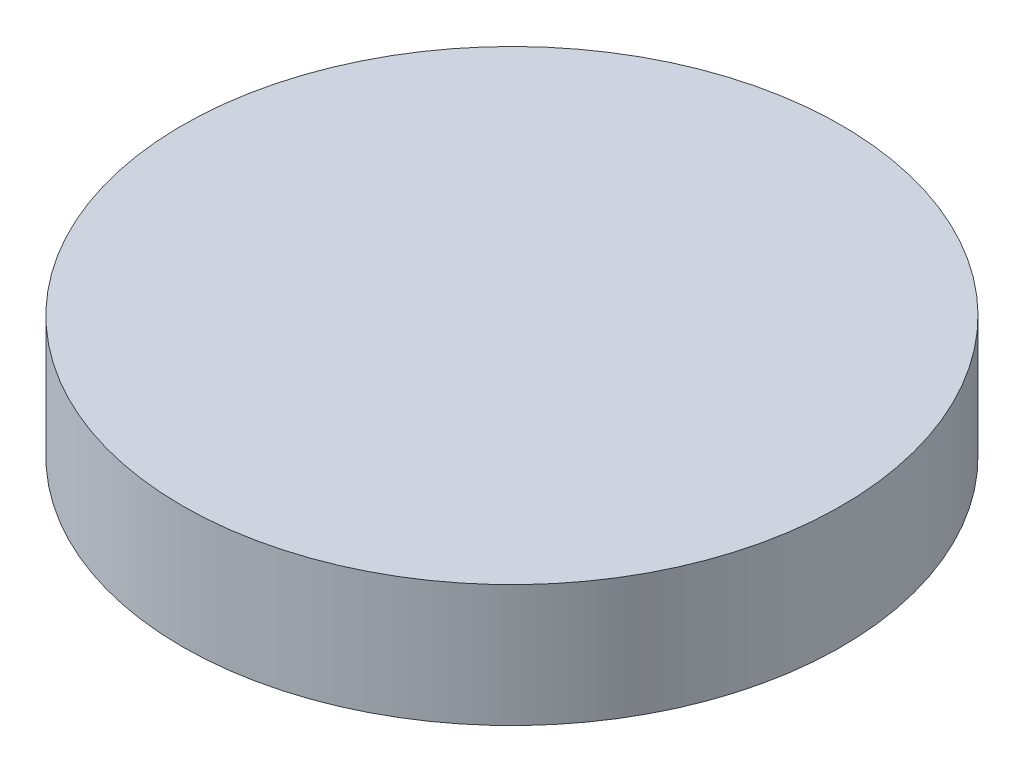
SolidWorks part; units mm, degrees
ref_plane "Front Plane" through (0, 0, 0) normal (0, 0, 1) x (1, 0, 0)
ref_plane "Top Plane" through (0, 0, 0) normal (0, 1, 0) x (1, 0, 0)
ref_plane "Right Plane" through (0, 0, 0) normal (1, 0, 0) x (0, 0, -1)
sketch "Sketch1" plane through (0, 0, 0) normal (0, 1, 0) x (1, 0, 0)
  circle A0 centre (0, 0) radius 17.145
  dimension "D1" = 34.29
extrude "Boss-Extrude1" add sketch "Sketch1" along normal blind 6.35
